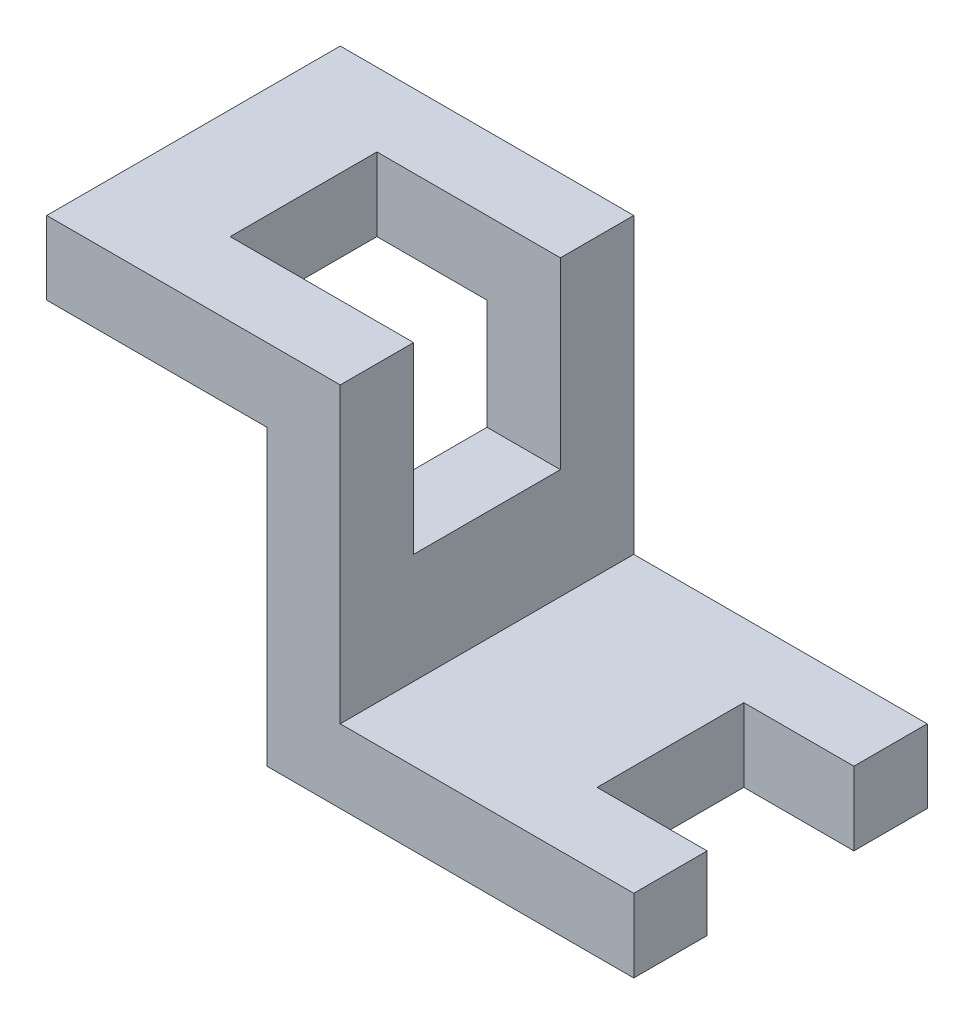
SolidWorks part; units mm, degrees
ref_plane "Plano frontal" through (0, 0, 0) normal (0, 0, 1) x (1, 0, 0)
ref_plane "Plano superior" through (0, 0, 0) normal (0, 1, 0) x (1, 0, 0)
ref_plane "Plano direito" through (0, 0, 0) normal (1, 0, 0) x (0, 0, -1)
sketch "Esboço1" plane through (0, 0, 0) normal (0, 0, 1) x (1, 0, 0)
  line L0 (-40, 0) -> (0, 0)
  line L1 (0, 0) -> (0, -40)
  line L2 (0, -40) -> (40, -40)
  line L3 (40, -40) -> (40, -50)
  line L4 (40, -50) -> (-10, -50)
  line L5 (-10, -50) -> (-10, -10)
  line L6 (-10, -10) -> (-40, -10)
  line L7 (-40, -10) -> (-40, 0)
  dimension "D1" = 40
  dimension "D2" = 50
  dimension "D3" = 40
  dimension "D4" = 40
  dimension "D5" = 10
  dimension "D6" = 10
  dimension "D7" = 10
extrude "Ressalto-extrusão1" add sketch "Esboço1" along normal blind 40
sketch "Esboço2" plane through (0, 0, 0) normal (1, 0, 0) x (0, 0, -1)
  line L0 (-30, 0) -> (-30, -25)
  line L1 (-40, 0) -> (0, 0) construction
  line L2 (-30, -25) -> (-10, -25)
  line L3 (-10, -25) -> (-10, 0)
  line L4 (-40, -40) -> (-40, 0) construction
  line L5 (0, -40) -> (0, 0) construction
  line L6 (-30, 0) -> (-10, 0)
  dimension "D1" = 10
  dimension "D2" = 25
  dimension "D3" = 10
extrude "Corte-extrusão1" cut sketch "Esboço2" against normal blind 25
sketch "Esboço3" plane through (0, -40, 0) normal (0, 1, 0) x (1, 0, 0)
  line L0 (40, -10) -> (25, -10)
  line L1 (40, -40) -> (40, 0) construction
  line L2 (25, -10) -> (25, -30)
  line L3 (25, -30) -> (40, -30)
  line L4 (40, 0) -> (0, 0) construction
  line L5 (40, -40) -> (0, -40) construction
  line L6 (40, -10) -> (40, -30)
  dimension "D1" = 15
  dimension "D2" = 10
  dimension "D3" = 10
  dimension "D4" = 20
extrude "Corte-extrusão2" cut sketch "Esboço3" against normal blind 25
